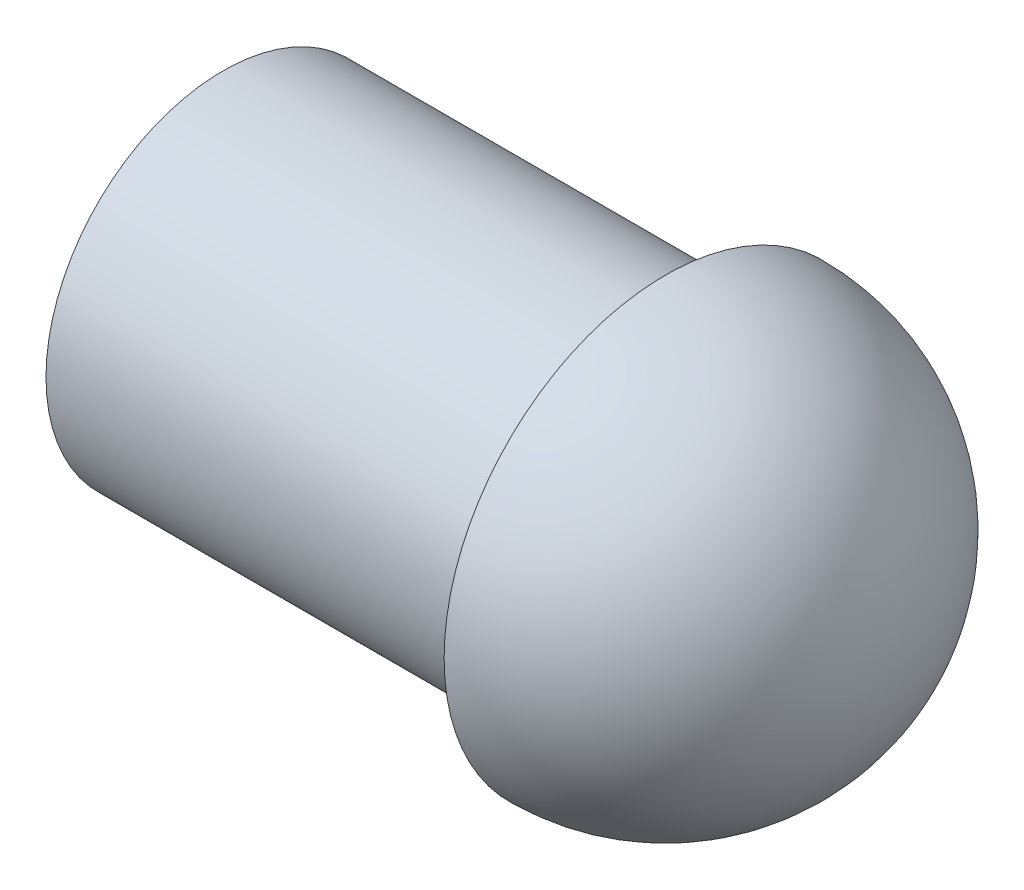
SolidWorks part; units mm, degrees
ref_plane "前基準面" through (0, 0, 0) normal (0, 0, 1) x (1, 0, 0)
ref_plane "上基準面" through (0, 0, 0) normal (0, 1, 0) x (1, 0, 0)
ref_plane "右基準面" through (0, 0, 0) normal (1, 0, 0) x (0, 0, -1)
sketch "草圖1" plane through (0, 0, 0) normal (1, 0, 0) x (0, 0, -1)
  line L0 (0, 25) -> (0, 0)
  arc A0 (0, 25) -> (0, 0) centre (0, 12.5) cw
  dimension "D1" = 25
revolve "旋轉1" add sketch "草圖1" angle 180 about L0
sketch "草圖2" plane through (0, 0, 0) normal (-1, 0, 0) x (0, 0, 1)
  circle A1 centre (0, 12.5) radius 2.5
  circle A2 centre (0, 12.5) radius 10
  dimension "D1" = 5
  dimension "D2" = 20
extrude "填料-伸長1" add sketch "草圖2" along normal blind 25
